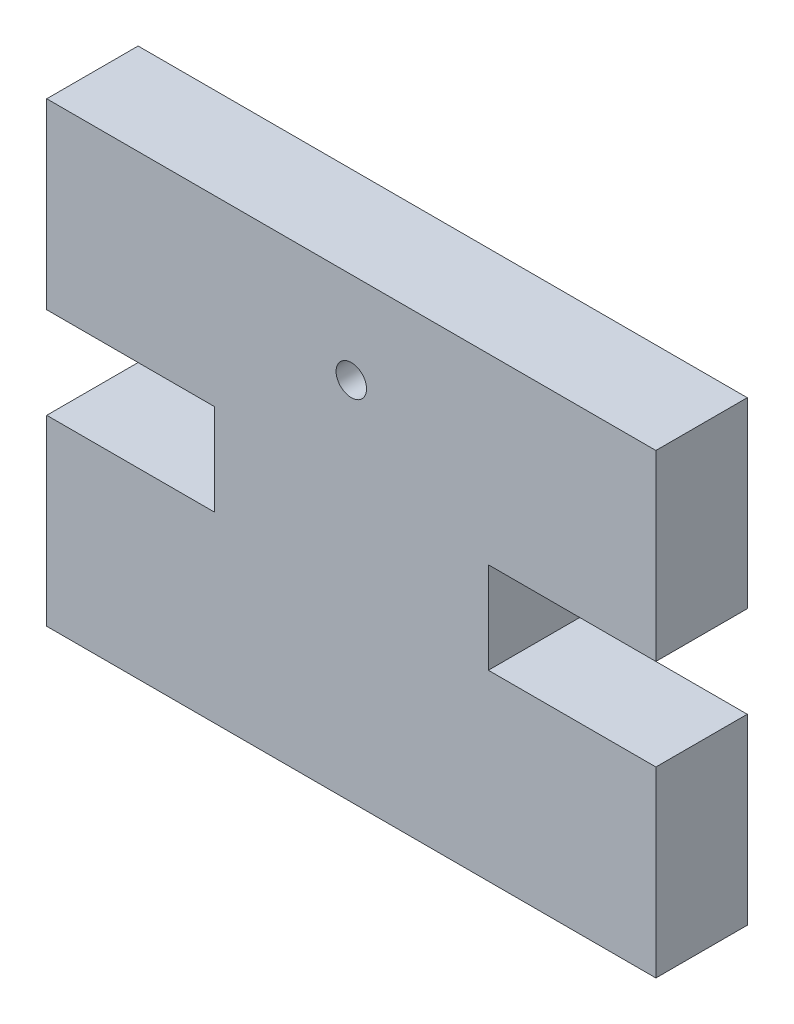
SolidWorks part; units mm, degrees
ref_plane "Front Plane" through (0, 0, 0) normal (0, 0, 1) x (1, 0, 0)
ref_plane "Top Plane" through (0, 0, 0) normal (0, 1, 0) x (1, 0, 0)
ref_plane "Right Plane" through (0, 0, 0) normal (1, 0, 0) x (0, 0, -1)
sketch "Sketch1" plane through (0, 0, 0) normal (0, 0, 1) x (1, 0, 0)
  line L1 (0, 0) -> (9, 0)
  line L2 (0, 0) -> (0, 3)
  line L4 (9, 0) -> (9, 3)
  line L5 (14.5, 9) -> (14.5, 3)
  line L6 (14.5, 3) -> (9, 3)
  line L7 (-5.5, 9) -> (-5.5, 3)
  line L8 (14.5, 9) -> (-5.5, 3) construction
  line L9 (14.5, 3) -> (-5.2679, 8.9304) construction
  line L10 (0, 3) -> (-5.5, 3)
  line L14 (-5.5, 9) -> (14.5, 9)
  circle A1 centre (4.5, 6) radius 0.5
  point P7 (4.5, 0)
  dimension "D3" = 1
  dimension "D4" = 3
  dimension "D1" = 9
  dimension "D2" = 6
  dimension "D5" = 3
  dimension "D7" = 20
extrude "Boss-Extrude1" add sketch "Sketch1" along normal blind 3
sketch "Sketch2" plane through (0, 0, 0) normal (0, -1, 0) x (1, 0, 0)
  line L0 (4.5, 0) -> (4.5, 3) construction
  line L1 (-5.5, 3) -> (14.5, 3)
  line L2 (-5.5, 3) -> (-5.5, 0)
  line L3 (-5.5, 0) -> (14.5, 0)
  line L4 (14.5, 3) -> (14.5, 0)
  line L5 (-5.5, 3) -> (14.5, 0) construction
  line L6 (-5.5, 0) -> (14.5, 3) construction
  line L7 (0, 0) -> (9, 0) construction
  point P0 (4.5, 1.5)
  point P9 (4.5, 0)
  dimension "D1" = 20
  dimension "D2" = 3
extrude "Boss-Extrude2" add sketch "Sketch2" along normal blind 6
